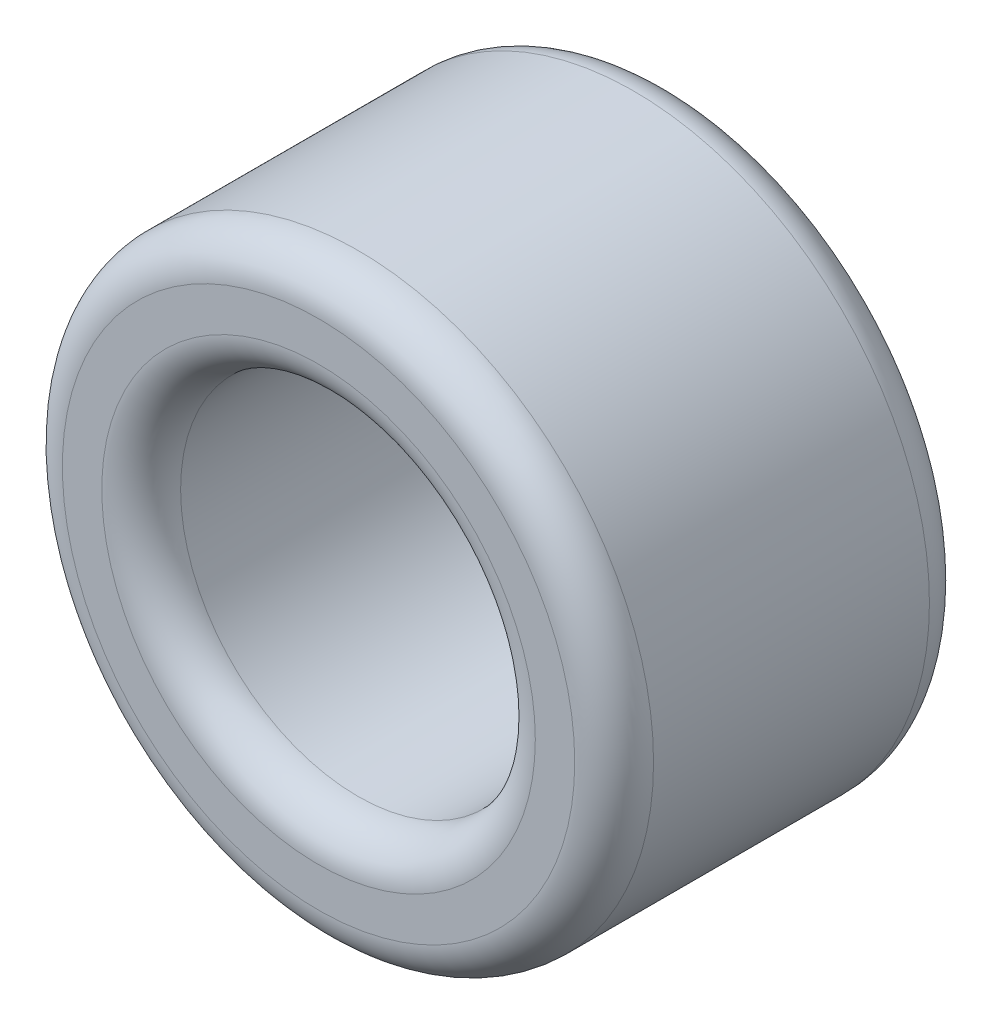
SolidWorks part; units mm, degrees
ref_plane "Front Plane" through (0, 0, 0) normal (0, 0, 1) x (1, 0, 0)
ref_plane "Top Plane" through (0, 0, 0) normal (0, 1, 0) x (1, 0, 0)
ref_plane "Right Plane" through (0, 0, 0) normal (1, 0, 0) x (0, 0, -1)
ref_plane "Plane1" through (0, 0, 58) normal (0, 0, 1) x (1, 0, 0)
sketch "Sketch1" plane through (0, 0, 58) normal (0, 0, 1) x (1, 0, 0)
  circle A0 centre (-4.04, 19.3257) radius 2.25
  circle A1 centre (-4.04, 19.3257) radius 3.75
  dimension "D1" = 7.5
  dimension "D2" = 4.5
extrude "Boss-Extrude2" add sketch "Sketch1" along normal mid plane 4.5
fillet "Fillet1" radius 0.5 4 edges at (-1.79, 19.3257, 55.75) (-1.79, 19.3257, 60.25) (-0.29, 19.3257, 55.75) (-0.29, 19.3257, 60.25)
